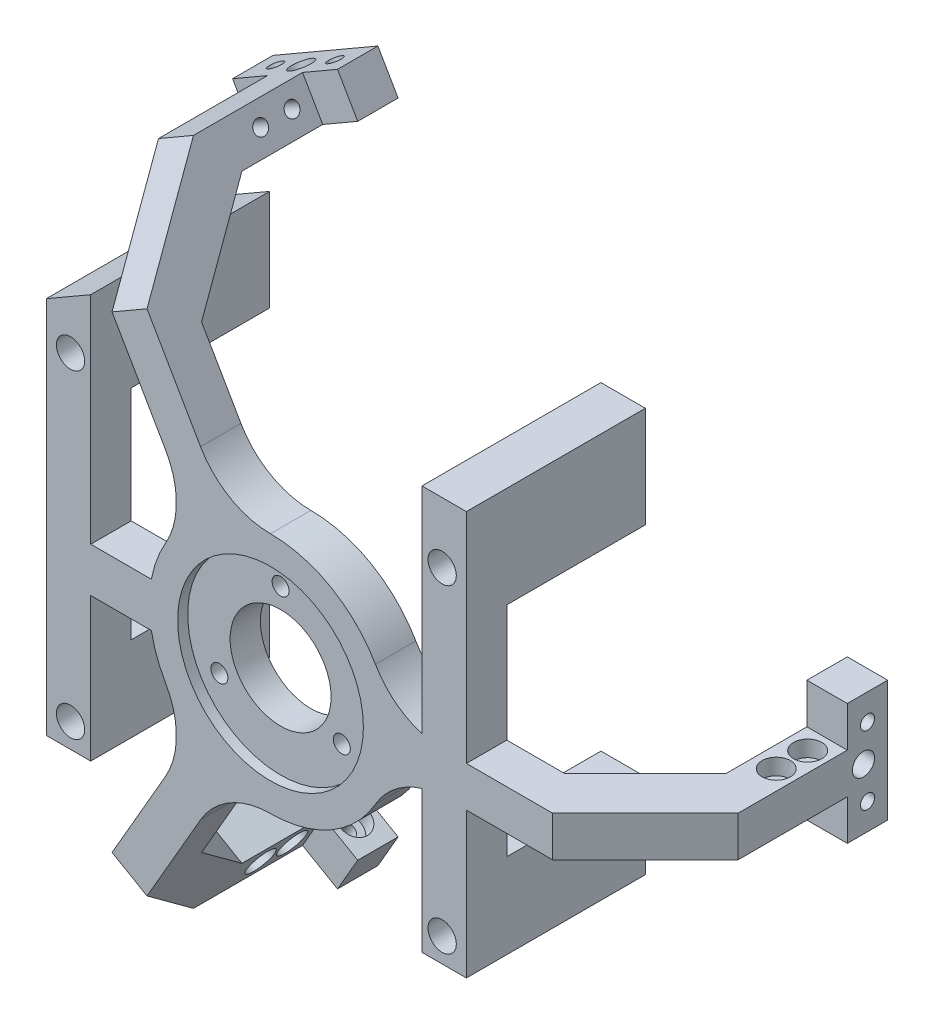
SolidWorks part; units mm, degrees
ref_plane "Plan de face" through (0, 0, 0) normal (0, 0, 1) x (1, 0, 0)
ref_plane "Plan de dessus" through (0, 0, 0) normal (0, 1, 0) x (1, 0, 0)
ref_plane "Plan de droite" through (0, 0, 0) normal (1, 0, 0) x (0, 0, -1)
sketch "Esquisse1" plane through (0, 0, 0) normal (0, 0, 1) x (1, 0, 0)
  line L0 (0, 0) -> (82.7955, 0) construction
  line L1 (82.7955, 15) -> (92.7955, 15)
  line L2 (82.7955, 15) -> (82.7955, -15)
  line L3 (82.7955, -15) -> (92.7955, -15)
  line L4 (92.7955, 15) -> (92.7955, -15)
  line L5 (-28.4074, -79.203) -> (-54.3881, -64.203)
  line L6 (-28.4074, -79.203) -> (-33.4074, -87.8632)
  line L7 (-33.4074, -87.8632) -> (-59.3881, -72.8632)
  line L8 (-54.3881, -64.203) -> (-59.3881, -72.8632)
  line L9 (-54.3881, 64.203) -> (-28.4074, 79.203)
  line L10 (-54.3881, 64.203) -> (-59.3881, 72.8632)
  line L11 (-59.3881, 72.8632) -> (-33.4074, 87.8632)
  line L12 (-28.4074, 79.203) -> (-33.4074, 87.8632)
  point P17 (0, 0)
  dimension "D1" = 30
  dimension "D2" = 10
  dimension "D3" = 82.7955
  dimension "D4" = 3
extrude "Boss.-Extru.1" add sketch "Esquisse1" along normal blind 10
sketch "Esquisse2" plane through (0, 0, 10) normal (0, 0, 1) x (1, 0, 0)
  line L0 (-51.5899, 77.3655) -> (-40.9159, 83.5282)
  line L1 (-33.4074, 87.8632) -> (-59.3881, 72.8632) construction
  line L2 (82.7955, 15) -> (82.7955, -15) construction
  line L3 (82.7955, 5) -> (92.7955, 5)
  line L4 (82.7955, 5) -> (82.7955, -5)
  line L5 (82.7955, -5) -> (92.7955, -5)
  line L6 (92.7955, 5) -> (92.7955, -5)
  line L7 (92.7955, -15) -> (92.7955, 15) construction
  line L8 (-37.0676, -74.203) -> (-45.7279, -69.203)
  line L9 (-37.0676, -74.203) -> (-42.0676, -82.8632)
  line L10 (-42.0676, -82.8632) -> (-50.7279, -77.8632)
  line L11 (-45.7279, -69.203) -> (-50.7279, -77.8632)
  line L12 (-45.7279, 69.203) -> (-37.0676, 74.203)
  line L13 (-45.7279, 69.203) -> (-50.7279, 77.8632)
  line L14 (-50.7279, 77.8632) -> (-42.0676, 82.8632)
  line L15 (-37.0676, 74.203) -> (-42.0676, 82.8632)
  point P12 (82.7955, 0)
  point P13 (82.7955, 0)
  point P24 (0, 0)
  line M6 (-54.3881, 64.203) -> (-28.4074, 79.203)
  dimension "D1" = 3
extrude "Boss.-Extru.2" add sketch "Esquisse2" along normal blind 40 contours L15 L0 L13 M6 | L6 L3 L4 L5 | L8 L11 L10 L9
sketch "Esquisse3" plane through (0, 0, 50) normal (0, 0, 1) x (1, 0, 0)
  line L0 (92.7955, 5) -> (92.7955, -5) construction
  line L1 (-42.0676, -82.8632) -> (-50.7279, -77.8632) construction
  line L2 (-42.0676, 82.8632) -> (-50.7279, 77.8632) construction
  line L3 (92.7955, 5) -> (92.7955, -5)
  line L4 (-42.0676, -82.8632) -> (-50.7279, -77.8632)
  line L5 (-42.0676, 82.8632) -> (-50.7279, 77.8632)
  line L6 (-50.7279, -77.8632) -> (-19.1203, -23.1174)
  line L7 (-42.0676, -82.8632) -> (-10.4601, -28.1174)
  line L8 (92.7955, -5) -> (29.5804, -5)
  line L9 (92.7955, 5) -> (29.5804, 5)
  line L10 (-50.7279, 77.8632) -> (-19.1203, 23.1174)
  line L11 (-42.0676, 82.8632) -> (-10.4601, 28.1174)
  line L12 (-45.7279, -69.203) -> (-50.7279, -77.8632) construction
  line L13 (-37.0676, -74.203) -> (-42.0676, -82.8632) construction
  line L14 (82.7955, -5) -> (92.7955, -5) construction
  line L15 (82.7955, 5) -> (92.7955, 5) construction
  line L16 (-45.7279, 69.203) -> (-50.7279, 77.8632) construction
  line L17 (-37.0676, 74.203) -> (-42.0676, 82.8632) construction
  arc A0 (-19.1203, -23.1174) -> (-19.1203, 23.1174) centre (0, 0) cw
  arc A1 (-10.4601, 28.1174) -> (29.5804, 5) centre (0, 0) cw
  arc A2 (29.5804, -5) -> (-10.4601, -28.1174) centre (0, 0) cw
  dimension "D1" = 30
extrude "Boss.-Extru.3" add sketch "Esquisse3" along normal blind 10
chamfer "Chanfrein1" distance 20 angle 45 3 edges at (82.7955, 0, 50) (-41.3977, -71.703, 50) (-41.3977, 71.703, 50)
chamfer "Chanfrein2" distance 23 angle 45 3 edges at (-46.3977, -80.3632, 60) (-46.3977, 80.3632, 60) (92.7955, 0, 60)
fillet "Congé1" radius 20 6 edges at (29.5804, -5, 55) (-10.4601, -28.1174, 55) (-19.1203, -23.1174, 55) (-19.1203, 23.1174, 55) (29.5804, 5, 55) (-10.4601, 28.1174, 55)
sketch "Esquisse4" plane through (0, 0, 60) normal (0, 0, 1) x (1, 0, 0)
  circle A0 centre (0, 0) radius 12.5
  dimension "D1" = 25
extrude "Enlèv. mat.-Extru.1" cut sketch "Esquisse4" against normal up to next
sketch "Esquisse5" plane through (0, 0, 60) normal (0, 0, 1) x (1, 0, 0)
  circle A0 centre (0, 0) radius 23
  dimension "D1" = 46
extrude "Enlèv. mat.-Extru.2" cut sketch "Esquisse5" against normal blind 2.5
sketch "Esquisse6" plane through (0, 0, 57.5) normal (0, 0, 1) x (1, 0, 0)
  line L0 (0, 17.5) -> (0, 0) construction
  circle A0 centre (0, 17.5) radius 2.1
  circle A1 centre (15.1554, -8.75) radius 2.1
  circle A2 centre (-15.1554, -8.75) radius 2.1
  point P10 (0, 0)
  dimension "D2" = 4.2
  dimension "D1" = 17.5
  dimension "D3" = 3
extrude "Enlèv. mat.-Extru.3" cut sketch "Esquisse6" against normal up to next
sketch "Esquisse7" plane through (0, 0, 50) normal (0, 0, -1) x (-1, 0, 0)
  line L0 (0, 0) -> (44.5, 0) construction
  line L1 (-37.5, -41) -> (-48.5, -41)
  line L2 (-37.5, -41) -> (-37.5, 59)
  line L3 (-37.5, 59) -> (-48.5, 59)
  line L4 (-48.5, -41) -> (-48.5, 59)
  line L5 (55.5, -41) -> (44.5, -41)
  line L6 (44.5, -41) -> (44.5, -5.5)
  line L7 (44.5, -5.5) -> (29.4915, -5.5)
  line L8 (55.5, -41) -> (55.5, 52.6491)
  line L9 (55.5, 52.6491) -> (44.5, 59)
  line L10 (44.5, 59) -> (44.5, 5.5)
  line L11 (44.5, 5.5) -> (29.4915, 5.5)
  line L12 (44.5, -5.5) -> (44.5, 5.5) construction
  line L13 (35.7279, 51.8825) -> (27.0676, 56.8825) construction
  arc A0 (25.9808, -15) -> (25.9808, 15) centre (0, 0) ccw construction
  arc A1 (29.4915, -5.5) -> (29.4915, 5.5) centre (0, 0) ccw
  point P7 (-43, 59)
  point P22 (44.5, 0)
  point P28 (50, 55.8246)
  dimension "D1" = 11
  dimension "D2" = 41
  dimension "D3" = 100
  dimension "D4" = 43
  dimension "D5" = 93
extrude "Boss.-Extru.4" add sketch "Esquisse7" along normal blind 34.3 and the other way up to surface other way up to face at (23, 0, 60)
sketch "Esquisse8" plane through (0, 0, 15.7) normal (0, 0, -1) x (-1, 0, 0)
  line L0 (-48.5, 9) -> (55.5, 9) construction
  line L1 (-48.5, 59) -> (-48.5, -41) construction
  line L2 (55.5, -41) -> (55.5, 52.6491) construction
  line L3 (49.5, 44) -> (-42.5, 44) construction
  line L4 (3.5, 9) -> (3.5, 44) construction
  line L5 (-48.5, -41) -> (-37.5, -41) construction
  circle A0 centre (49.5, 44) radius 1.75
  circle A1 centre (-42.5, 44) radius 1.75
  circle A2 centre (-42.5, -35) radius 1.75
  circle A3 centre (49.5, -35) radius 1.75
  dimension "D4" = 3.5
  dimension "D1" = 92
  dimension "D2" = 79
  dimension "D3" = 6
extrude "Enlèv. mat.-Extru.4" cut sketch "Esquisse8" against normal up to next
sketch "Esquisse9" plane through (0, 0, 60) normal (0, 0, 1) x (1, 0, 0)
  circle A0 centre (42.5, -35) radius 3.5
  circle A1 centre (42.5, 44) radius 3.5
  circle A2 centre (-49.5, -35) radius 3.5
  circle A3 centre (-49.5, 44) radius 3.5
  dimension "D1" = 7
extrude "Enlèv. mat.-Extru.5" cut sketch "Esquisse9" against normal offset from surface (23.3 mm away) 21 up to face at (40.75, -35, 15.7)
sketch "Esquisse10" plane through (0, 0, 15.7) normal (0, 0, -1) x (-1, 0, 0)
  line L0 (-48.5, 59) -> (-48.5, -41) construction
  line L1 (-48.5, 34) -> (55.5, 34)
  line L2 (-48.5, 34) -> (-48.5, -20)
  line L3 (-48.5, -20) -> (55.5, -20)
  line L4 (55.5, 34) -> (55.5, -20)
  line L5 (55.5, -41) -> (55.5, 52.6491) construction
  circle A0 centre (49.5, 44) radius 1.75 construction
  circle A1 centre (49.5, -35) radius 1.75 construction
  dimension "D1" = 10
  dimension "D2" = 15
extrude "Enlèv. mat.-Extru.6" cut sketch "Esquisse10" against normal up to surface (34.3 mm away) up to face at (-10.6964, 0, 50)
sketch "Esquisse11" plane through (4.3301, -2.5, 0) normal (0.866, -0.5, 0) x (0, 0, -1)
  line L0 (-30, -82.7955) -> (-10, -82.7955) construction
  line L1 (-10, -82.7955) -> (-10, -92.7955) construction
  circle A0 centre (-15, -87.9855) radius 1.75
  circle A1 centre (-22.78, -87.9855) radius 1.75
  dimension "D4" = 3.5
  dimension "D1" = 5.19
  dimension "D2" = 5
  dimension "D3" = 7.78
extrude "Enlèv. mat.-Extru.7" cut sketch "Esquisse11" against normal up to next
sketch "Esquisse12" plane through (4.3301, -2.5, 0) normal (0.866, -0.5, 0) x (0, 0, -1)
  circle A0 centre (-15, -87.9855) radius 3.5
  circle A1 centre (-22.78, -87.9855) radius 3.5
  dimension "D1" = 7
extrude "Enlèv. mat.-Extru.8" cut sketch "Esquisse12" against normal blind 4
sketch "Esquisse13" plane through (-41.3977, -71.703, 0) normal (0.5, 0.866, 0) x (0.866, -0.5, 0)
  line L0 (-15, -10) -> (-15, 0) construction
  line L1 (-15, -5) -> (-8.5, -5) construction
  line L2 (15, -5) -> (8.5, -5) construction
  line L3 (15, -10) -> (15, 0) construction
  circle A0 centre (-8.5, -5) radius 1.75
  circle A1 centre (8.5, -5) radius 1.75
  dimension "D2" = 3.5
  dimension "D1" = 6.5
extrude "Enlèv. mat.-Extru.9" cut sketch "Esquisse13" against normal up to next
sketch "Esquisse14" plane through (-41.3977, -71.703, 0) normal (0.5, 0.866, 0) x (0.866, -0.5, 0)
  circle A0 centre (-8.5, -5) radius 3.5
  circle A1 centre (8.5, -5) radius 3.5
  dimension "D1" = 7
extrude "Enlèv. mat.-Extru.10" cut sketch "Esquisse14" against normal blind 4
sketch "Esquisse15" plane through (-41.3977, -71.703, 0) normal (0.5, 0.866, 0) x (0.866, -0.5, 0)
  line L0 (15, 0) -> (-15, 0) construction
  line L1 (-15, -10) -> (-15, 0) construction
  circle A0 centre (0, -6) radius 2.75
  point P5 (0, 0)
  point P8 (-15, -5)
  dimension "D1" = 5.5
  dimension "D2" = 1
extrude "Enlèv. mat.-Extru.11" cut sketch "Esquisse15" against normal up to next
pattern_circular "Répétition circulaire1" count 3 over 360 about axis through (0, 0, 0) along (0, 0, 1) of "Enlèv. mat.-Extru.7", "Enlèv. mat.-Extru.11", "Enlèv. mat.-Extru.10", "Enlèv. mat.-Extru.9", "Enlèv. mat.-Extru.8"
